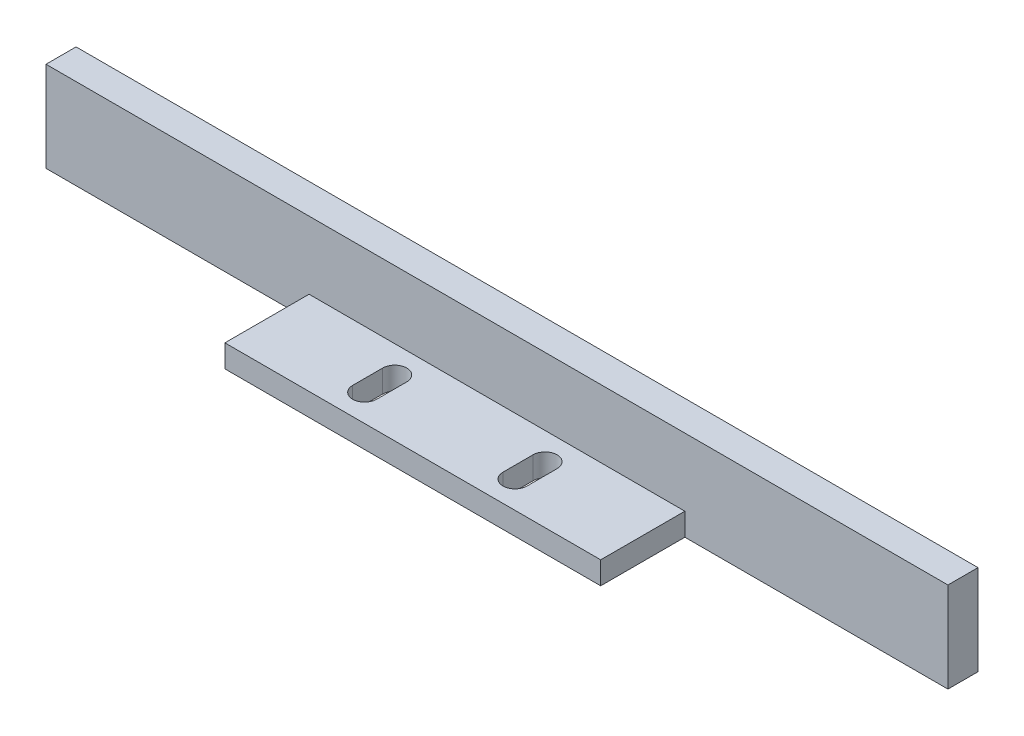
SolidWorks part; units mm, degrees
ref_plane "Front Plane" through (0, 0, 0) normal (0, 0, 1) x (1, 0, 0)
ref_plane "Top Plane" through (0, 0, 0) normal (0, 1, 0) x (1, 0, 0)
ref_plane "Right Plane" through (0, 0, 0) normal (1, 0, 0) x (0, 0, -1)
sketch "Sketch1" plane through (0, 0, 0) normal (0, 0, 1) x (1, 0, 0)
  line L1 (-63.7674, 34.5965) -> (56.2326, 34.5965)
  line L2 (-63.7674, 34.5965) -> (-63.7674, 22.5965)
  line L3 (-63.7674, 22.5965) -> (56.2326, 22.5965)
  line L4 (56.2326, 34.5965) -> (56.2326, 22.5965)
  dimension "D1" = 120
  dimension "D2" = 12
extrude "Boss-Extrude1" add sketch "Sketch1" along normal blind 4
ref_plane "Plane1" through (0, 0, 4) normal (0, 0, 1) x (1, 0, 0)
sketch "Sketch2" plane through (0, 0, 4) normal (0, 0, 1) x (1, 0, 0)
  line L0 (-3.7674, 22.5965) -> (21.2326, 22.5965)
  line L1 (-63.7674, 22.5965) -> (56.2326, 22.5965) construction
  line L2 (21.2326, 22.5965) -> (21.2326, 25.5965)
  line L3 (21.2326, 25.5965) -> (-28.7674, 25.5965)
  line L4 (-28.7674, 25.5965) -> (-28.7674, 22.5965)
  line L5 (-28.7674, 22.5965) -> (-3.7674, 22.5965)
  dimension "D1" = 25
  dimension "D2" = 3
  dimension "D3" = 50
extrude "Boss-Extrude2" add sketch "Sketch2" along normal blind 11.2
ref_plane "Plane2" through (0, 25.5965, 0) normal (0, 1, 0) x (1, 0, 0)
sketch "Sketch3" plane through (0, 25.5965, 0) normal (0, 1, 0) x (1, 0, 0)
  line L3 (-13.7674, -6) -> (-13.7674, -7.6)
  line L4 (7.8326, -11.6) -> (7.8326, -7.6)
  line L5 (4.6326, -7.6) -> (4.6326, -11.6)
  line L7 (-15.3674, -7.6) -> (-15.3674, -11.6)
  line L8 (-12.1674, -7.6) -> (-12.1674, -11.6)
  arc A0 (7.8326, -7.6) -> (4.6326, -7.6) centre (6.2326, -7.6) ccw
  arc A1 (4.6326, -11.6) -> (7.8326, -11.6) centre (6.2326, -11.6) ccw
  arc A2 (-12.1674, -7.6) -> (-15.3674, -7.6) centre (-13.7674, -7.6) ccw
  arc A3 (-15.3674, -11.6) -> (-12.1674, -11.6) centre (-13.7674, -11.6) ccw
  dimension "D3" = 3.2
  dimension "D5" = 3.2
  dimension "D6" = 3.2
  dimension "D8" = 3.2
  dimension "D4" = 4
  dimension "D7" = 4
extrude "Cut-Extrude1" cut sketch "Sketch3" against normal blind 3
